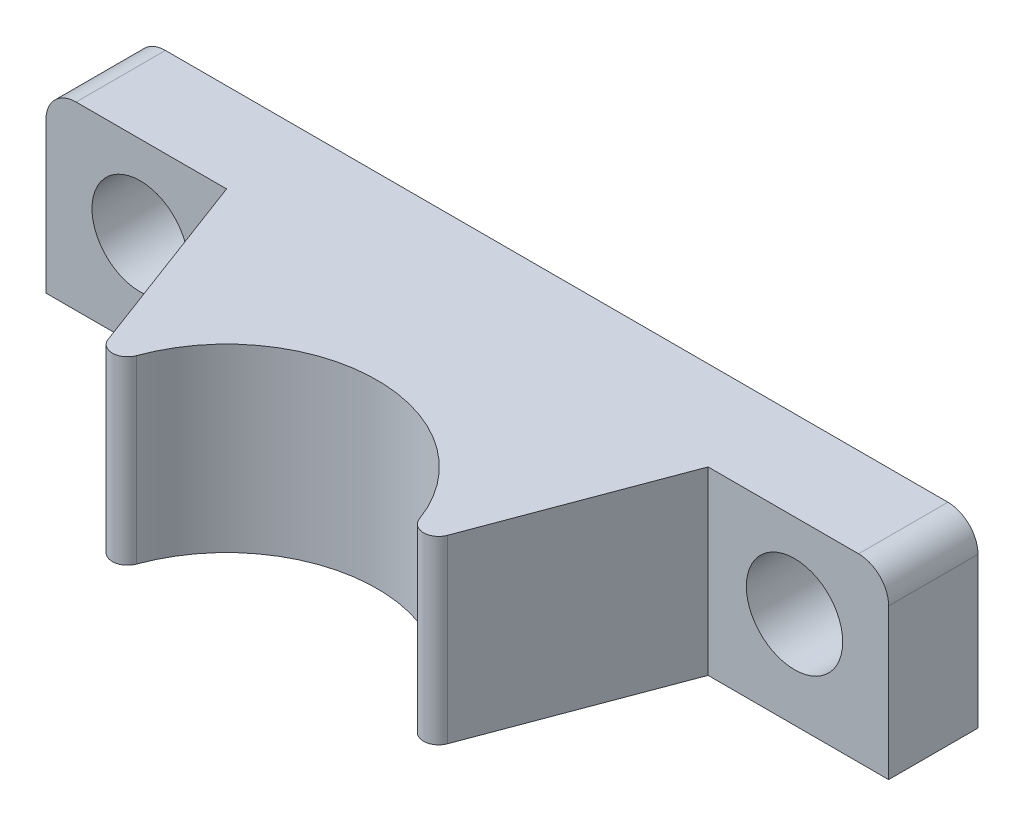
SolidWorks part; units mm, degrees
ref_plane "Front Plane" through (0, 0, 0) normal (0, 0, 1) x (1, 0, 0)
ref_plane "Top Plane" through (0, 0, 0) normal (0, 1, 0) x (1, 0, 0)
ref_plane "Right Plane" through (0, 0, 0) normal (1, 0, 0) x (0, 0, -1)
sketch "Sketch1" plane through (0, 41.4635, 0) normal (0, 1, 0) x (1, 0, 0)
  line L0 (26.6144, -46.1716) -> (23.6144, -38.1716)
  line L2 (39.6144, -38.1716) -> (36.6144, -46.1716)
  line L3 (39.6144, -38.1716) -> (45.6144, -38.1716)
  line L4 (17.6144, -38.1716) -> (23.6144, -38.1716)
  line L5 (17.6144, -38.1716) -> (17.6144, -35.2026)
  line L6 (17.6144, -35.2026) -> (45.6144, -35.2026)
  line L7 (45.6144, -38.1716) -> (45.6144, -35.2026)
  arc A0 (36.6144, -46.1716) -> (26.6144, -46.1716) centre (31.6144, -46.1716) ccw
  dimension "D1" = 28
  dimension "D2" = 14
extrude "Boss-Extrude1" add sketch "Sketch1" against normal up to vertex (6 mm away)
fillet "Fillet1" radius 1 2 edges at (17.6144, 41.4635, 36.6871) (45.6144, 41.4635, 36.6871)
fillet "Fillet2" radius 0.5 2 edges at (36.6144, 38.4635, 46.1716) (26.6144, 38.4635, 46.1716)
sketch "Sketch2" plane through (0, 0, 35.2026) normal (0, 0, -1) x (-1, 0, 0)
  circle A0 centre (-20.7421, 38.6635) radius 1.6
  circle A1 centre (-42.4866, 38.6635) radius 1.6
extrude "Cut-Extrude2" cut sketch "Sketch2" against normal blind 10
